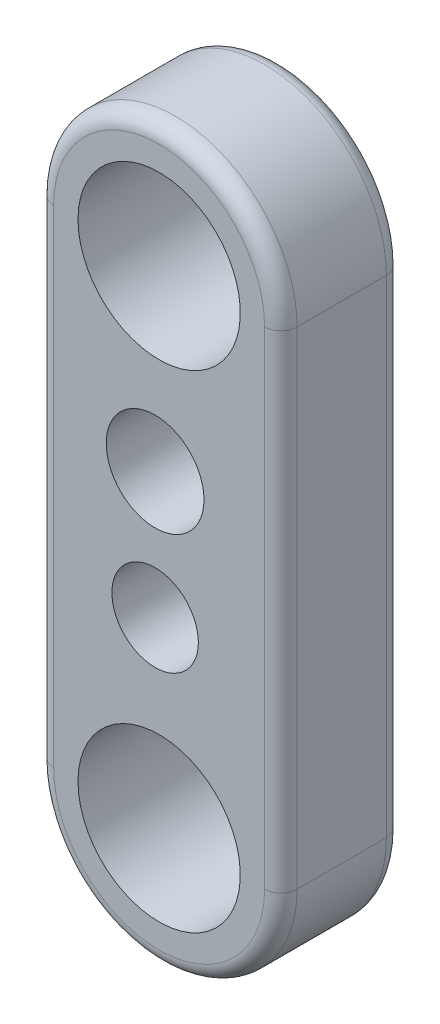
SolidWorks part; units mm, degrees
material "ASTM A36 Steel"
ref_plane "Front Plane" through (0, 0, 0) normal (0, 0, 1) x (1, 0, 0)
ref_plane "Top Plane" through (0, 0, 0) normal (0, 1, 0) x (1, 0, 0)
ref_plane "Right Plane" through (0, 0, 0) normal (1, 0, 0) x (0, 0, -1)
sketch "Sketch1" plane through (0, 0, 0) normal (0, 0, 1) x (1, 0, 0)
  line L0 (-29.7399, 28.1638) -> (-29.7399, -48.0362)
  line L1 (8.3601, 28.1638) -> (8.3601, -48.0362)
  arc A0 (-29.7399, 28.1638) -> (8.3601, 28.1638) centre (-10.6899, 28.1638) cw
  arc A1 (-29.7399, -48.0362) -> (8.3601, -48.0362) centre (-10.6899, -48.0362) ccw
  circle A2 centre (-10.6899, 28.1638) radius 12.7
  circle A3 centre (-10.6899, -48.0362) radius 12.7
  point P8 (0, 0)
  dimension "D1" = 76.2
  dimension "D3" = 25.4
  dimension "D4" = 25.4
  dimension "D2" = 38.1
extrude "Boss-Extrude2" add sketch "Sketch1" along normal blind 19.05 contours A0 L1 A1 L0
sketch "Sketch2" plane through (0, 0, 0) normal (0, 0, -1) x (-1, 0, 0)
  circle A0 centre (10.6899, 28.1638) radius 12.7
  circle A2 centre (10.6899, -48.0362) radius 12.7
  dimension "D1" = 25.4
  dimension "D2" = 25.4
extrude "Cut-Extrude1" cut sketch "Sketch2" against normal through all
ref_plane "Plane1" through (0, 28.1638, 0) normal (0, -1, 0) x (-1, 0, 0)
ref_plane "Plane2" through (0, 28.1638, 0) normal (0, -1, 0) x (-1, 0, 0)
ref_point "Point1"
fillet "Fillet1" radius 2.54 4 edges at (-29.7399, -9.9362, 19.05) (-10.6899, -67.0862, 19.05) (8.3601, -9.9362, 19.05) (-10.6899, 47.2138, 19.05)
fillet "Fillet2" radius 2.54 4 edges at (-29.7399, -9.9362, 0) (-10.6899, 47.2138, 0) (8.3601, -9.9362, 0) (-10.6899, -67.0862, 0)
sketch "Sketch9" plane through (0, 0, 19.05) normal (0, 0, 1) x (1, 0, 0)
  circle A0 centre (-11.3201, 0) radius 7.6511
  circle A1 centre (-11.3201, -19.7936) radius 6.7666
extrude "Cut-Extrude7" cut sketch "Sketch9" against normal through all
equation "\"Link length\"= 3"
equation "\"Anet\"= 0.125"
equation "\"width\"= 1.50"
equation "\"extrude\"= 1 / 4"
equation "\"actual width\"= ( \"Anet\" / \"extrude\" ) + 1.00"
equation "\"D1\" = \"Link length\""
equation "\"D2\" = \"actual width\""
equation "\"diameter\"= ( \"Anet\" / \"extrude\" - \"actual width\" ) / - 1.00"
equation "\"D4\"= 0"
equation "\"d3\" = 0"
equation "\"D1@Boss-Extrude2\"=\"extrude\""
equation "\"D1@Sketch2\"=\"diameter\""
equation "\"D2@Sketch2\"=\"diameter\""
equation "\"D1@Sketch3\" = \""
